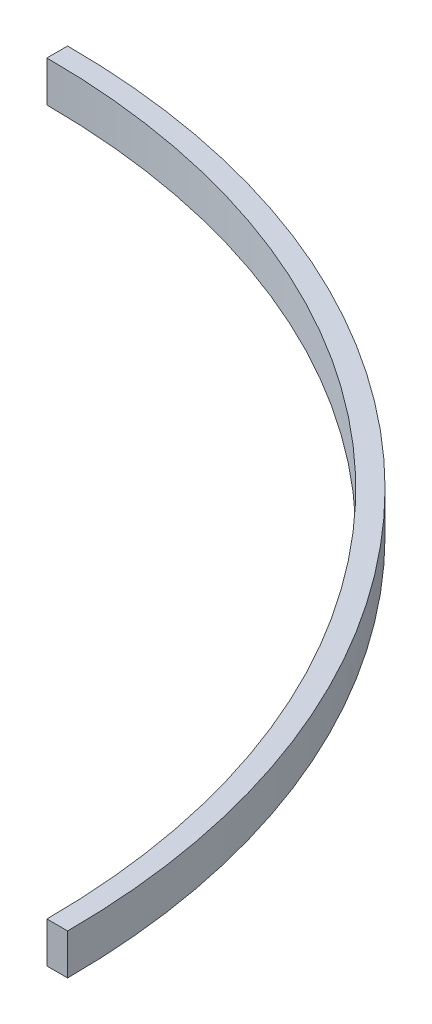
SolidWorks part; units mm, degrees
ref_plane "Front Plane" through (0, 0, 0) normal (0, 0, 1) x (1, 0, 0)
ref_plane "Top Plane" through (0, 0, 0) normal (0, 1, 0) x (1, 0, 0)
ref_plane "Right Plane" through (0, 0, 0) normal (1, 0, 0) x (0, 0, -1)
sketch "Sketch1" plane through (0, 0, 0) normal (0, 1, 0) x (1, 0, 0)
  line L0 (0, 0) -> (0, 470)
  line L1 (0, 0) -> (470, 0)
  circle A0 centre (0, 0) radius 470
  circle A1 centre (0, 0) radius 457.3
  dimension "D1" = 940
  dimension "D2" = 12.7
extrude "Boss-Extrude1" add sketch "Sketch1" along normal blind 25 contours A1 L1 A0 L0
